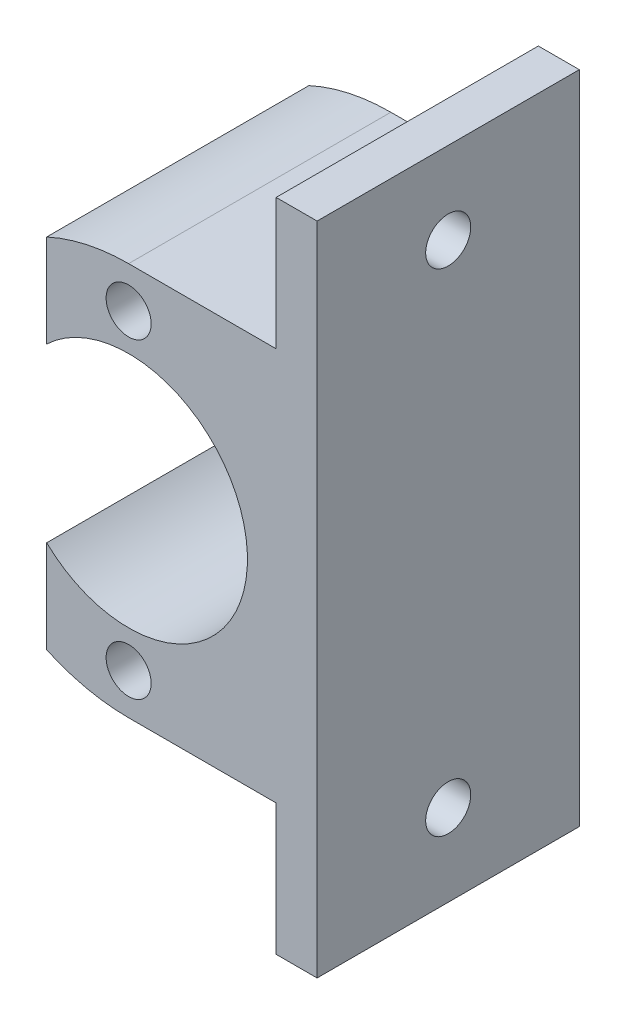
SolidWorks part; units mm, degrees
ref_plane "Plan de face" through (0, 0, 0) normal (0, 0, 1) x (1, 0, 0)
ref_plane "Plan de dessus" through (0, 0, 0) normal (0, 1, 0) x (1, 0, 0)
ref_plane "Plan de droite" through (0, 0, 0) normal (1, 0, 0) x (0, 0, -1)
sketch "Esquisse2" plane through (0, 0, 0) normal (0, 0, 1) x (1, 0, 0)
  line L2 (-5.4873, 19.9782) -> (17.5127, 19.9782)
  line L5 (17.5127, -28.0218) -> (-5.4873, -28.0218)
  line L8 (17.5127, 19.9782) -> (17.5127, -28.0218)
  line L9 (-15.4873, 17.7956) -> (-15.4873, 6.4782)
  line L10 (-15.4873, -14.5218) -> (-15.4873, -25.8392)
  arc A2 (-15.4873, 17.7956) -> (-5.4873, 19.9782) centre (-5.4873, -4.0218) cw
  arc A3 (-15.4873, -25.8392) -> (-5.4873, -28.0218) centre (-5.4873, -4.0218) ccw
  circle A4 centre (-5.4873, -4.0218) radius 19 construction
  circle A5 centre (-5.4873, 14.9782) radius 2.75
  circle A8 centre (-5.4873, -23.0218) radius 2.75
  arc A13 (-15.4873, 6.4782) -> (-15.4873, -14.5218) centre (-5.4873, -4.0218) cw
  dimension "D2" = 24
  dimension "D3" = 38
  dimension "D4" = 5.5
  dimension "D5" = 14.5
  dimension "D1" = 10
  dimension "D7" = 23
extrude "Boss.-Extru.1" add sketch "Esquisse2" along normal blind 32
sketch "Esquisse3" plane through (17.5127, 0, 0) normal (1, 0, 0) x (0, 0, -1)
  line L0 (0, -28.0218) -> (0, 19.9782) construction
  line L1 (-32, 19.9782) -> (0, 19.9782)
  line L2 (-32, 19.9782) -> (-32, 35.9782)
  line L3 (-32, 35.9782) -> (0, 35.9782)
  line L4 (0, 19.9782) -> (0, 35.9782)
  line L5 (-32, -28.0218) -> (0, -28.0218)
  line L6 (-32, -28.0218) -> (-32, -44.0218)
  line L7 (-32, -44.0218) -> (0, -44.0218)
  line L8 (0, -28.0218) -> (0, -44.0218)
  line L9 (-16, 25.9782) -> (-16, -34.0218) construction
  line L10 (-32, -28.0218) -> (-32, 19.9782) construction
  circle A0 centre (-16, 25.9782) radius 2.75
  circle A1 centre (-16, -34.0218) radius 2.75
  point P16 (-16, -4.0218)
  point P19 (-32, -4.0218)
  point P20 (-17.7336, 25.9782)
  point P21 (-16, 35.9782)
  dimension "D1" = 5.5
  dimension "D2" = 60
  dimension "D3" = 10
extrude "Boss.-Extru.2" add sketch "Esquisse3" against normal blind 5
